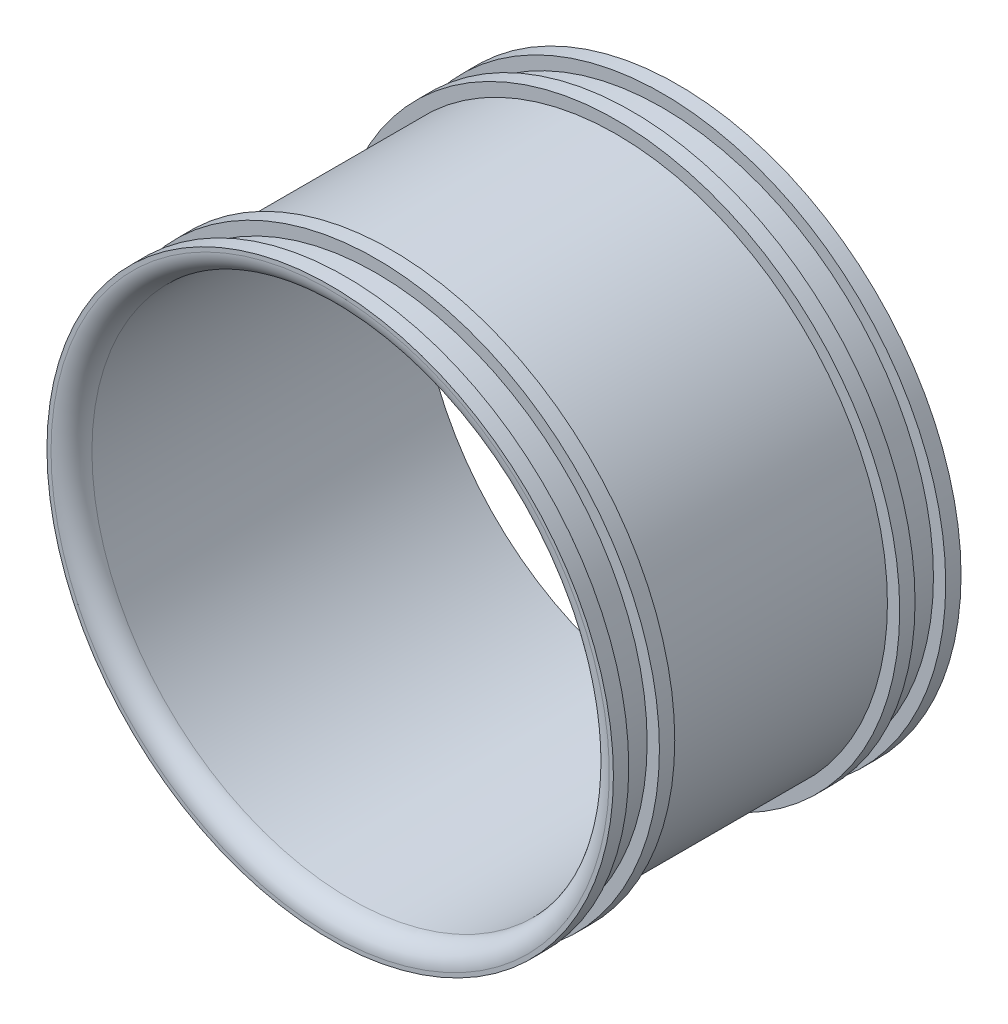
SolidWorks part; units mm, degrees
ref_plane "Front Plane" through (0, 0, 0) normal (0, 0, 1) x (1, 0, 0)
ref_plane "Top Plane" through (0, 0, 0) normal (0, 1, 0) x (1, 0, 0)
ref_plane "Right Plane" through (0, 0, 0) normal (1, 0, 0) x (0, 0, -1)
ref_plane "Plane1" through (0, 0, 0) normal (0, -1, 0) x (1, 0, 0)
sketch "Sketch1" plane through (0, 0, 0) normal (0, -1, 0) x (1, 0, 0)
  line L1 (0, 34) -> (0, 0) construction
  line L2 (25.3, 0) -> (27.7, 0)
  line L3 (27.7, 0) -> (27.7, 1.5)
  line L4 (27.7, 1.5) -> (26.5, 1.5)
  line L5 (26.5, 1.5) -> (26.5, 4.5)
  line L6 (26.5, 4.5) -> (27.7, 4.5)
  line L7 (27.7, 4.5) -> (27.7, 6)
  line L8 (27.7, 6) -> (26.5, 6)
  line L9 (26.5, 6) -> (26.5, 28)
  line L10 (26.5, 28) -> (27.7, 28)
  line L11 (27.7, 28) -> (27.7, 29.5)
  line L12 (27.7, 29.5) -> (26.5, 29.5)
  line L13 (26.5, 29.5) -> (26.5, 32.5)
  line L14 (26.5, 32.5) -> (27.7, 32.5)
  line L15 (27.7, 32.5) -> (27.7, 34)
  line L16 (0, 34) -> (0, 0) construction
  line L17 (25.3, 0) -> (25.3, 32)
  line L19 (0, 0) -> (25, 0) construction
  line L20 (27.3, 34) -> (27.7, 34)
  arc A0 (25.3, 32) -> (27.3, 34) centre (27.3, 32) cw
  dimension "D5" = 2
  dimension "D1" = 1.5
  dimension "D2" = 1.2
  dimension "D3" = 3
  dimension "D6" = 32
  dimension "D7" = 25
revolve "Revolve1" add sketch "Sketch1" angle 360 about L16
sketch "Sketch2" plane through (0, 0, 0) normal (0, -1, 0) x (1, 0, 0)
  line L0 (27.3, 34) -> (0, 34)
  line L1 (0, 34) -> (0, 0)
  line L2 (0, 0) -> (25.3, 0)
  line L3 (25.3, 0) -> (25.3, 32)
  line L4 (0, 34) -> (0, 0) construction
  arc A0 (25.3, 32) -> (27.3, 34) centre (27.3, 32) cw
